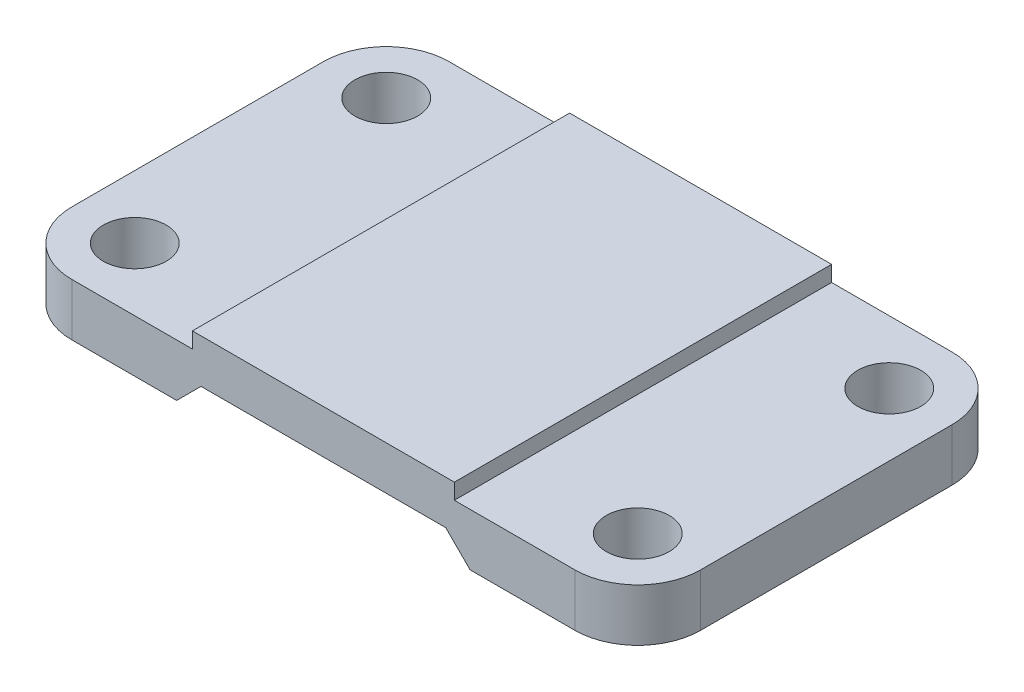
SolidWorks part; units mm, degrees
ref_plane "Front Plane" through (0, 0, 0) normal (0, 0, 1) x (1, 0, 0)
ref_plane "Top Plane" through (0, 0, 0) normal (0, 1, 0) x (1, 0, 0)
ref_plane "Right Plane" through (0, 0, 0) normal (1, 0, 0) x (0, 0, -1)
sketch "Sketch1" plane through (0, 0, 0) normal (0, 0, 1) x (1, 0, 0)
  line L12 (0, 0) -> (0, 10)
  line L13 (0, 10) -> (35, 10)
  line L14 (35, 10) -> (35, 13)
  line L15 (35, 13) -> (85, 13)
  line L16 (85, 13) -> (85, 10)
  line L17 (85, 10) -> (120, 10)
  line L18 (120, 10) -> (120, 0)
  line L19 (120, 0) -> (88, 0)
  line L21 (83.3492, 4.6508) -> (36.6508, 4.6508)
  line L23 (32, 0) -> (0, 0)
  line L24 (36.6508, 4.6508) -> (32, 0)
  line L25 (83.3492, 4.6508) -> (88, 0)
  dimension "D1" = 10
  dimension "D2" = 10
  dimension "D3" = 35
  dimension "D4" = 35
  dimension "D5" = 32
  dimension "D6" = 32
  dimension "D7" = 50
  dimension "D8" = 3
  dimension "D9" = 45
  dimension "D10" = 45
extrude "Boss-Extrude1" add sketch "Sketch1" along normal blind 72
sketch "Sketch3" plane through (0, 10, 0) normal (0, 1, 0) x (1, 0, 0)
  line L1 (12, 0) -> (108, 0)
  line L2 (0, -12) -> (0, -60)
  line L3 (12, -72) -> (108, -72)
  line L4 (120, -12) -> (120, -60)
  line L5 (0, 0) -> (120, 0)
  line L6 (0, 0) -> (0, -72)
  line L7 (0, -72) -> (120, -72)
  line L8 (120, 0) -> (120, -72)
  arc A0 (108, 0) -> (120, -12) centre (108, -12) cw
  arc A1 (108, -72) -> (120, -60) centre (108, -60) ccw
  arc A2 (0, -60) -> (12, -72) centre (12, -60) ccw
  arc A3 (12, 0) -> (0, -12) centre (12, -12) ccw
  circle A4 centre (12, -12) radius 6
  circle A5 centre (108, -12) radius 6
  circle A6 centre (12, -60) radius 6
  circle A7 centre (108, -60) radius 6
  point P10 (120, -72)
  point P15 (0, 0)
  point P24 (0, 0)
  line M1 (35, 0) -> (0, 0)
  line M2 (0, 0) -> (0, -72)
  line M3 (0, -72) -> (35, -72)
  dimension "D1" = 12
extrude "Cut-Extrude1" cut sketch "Sketch3" against normal blind 72 contours A4 | A5 | A7 | A6 | A3 M1 M2 | A2 M2 M3 | A1 L7 L8 | L5 A0 L8
